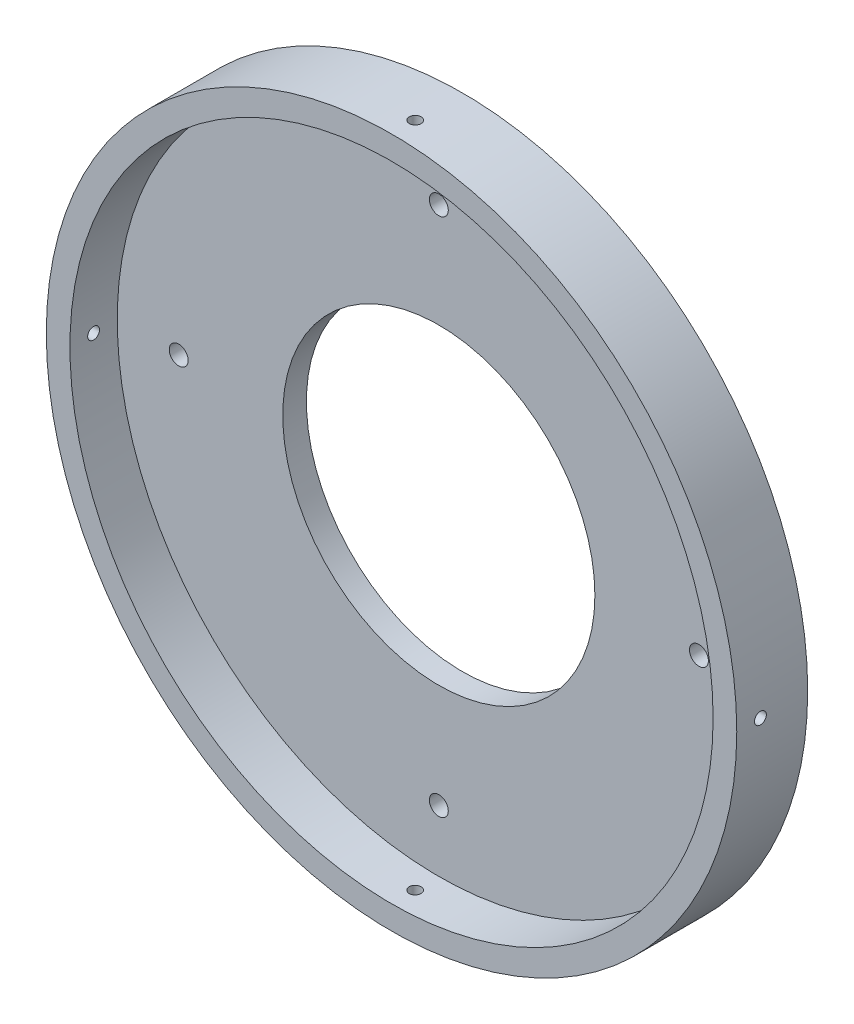
SolidWorks part; units mm, degrees
ref_plane "Front Plane" through (0, 0, 0) normal (0, 0, 1) x (1, 0, 0)
ref_plane "Top Plane" through (0, 0, 0) normal (0, 1, 0) x (1, 0, 0)
ref_plane "Right Plane" through (0, 0, 0) normal (1, 0, 0) x (0, 0, -1)
sketch "Sketch1" plane through (0, 0, 0) normal (0, 0, 1) x (1, 0, 0)
  circle A0 centre (0, 0) radius 73
  circle A1 centre (0, 0) radius 33
  dimension "D1" = 146
  dimension "D2" = 40
extrude "Boss-Extrude1" add sketch "Sketch1" along normal blind 5
sketch "Sketch2" plane through (0, 0, 5) normal (0, 0, 1) x (1, 0, 0)
  circle A0 centre (0, 0) radius 68
  circle A1 centre (0, 0) radius 73
  circle A2 centre (0, 0) radius 73
  dimension "D1" = 0
  dimension "D2" = 5
extrude "Boss-Extrude2" add sketch "Sketch2" along normal blind 10
sketch "Sketch3" plane through (0, 0, 0) normal (0, 1, 0) x (1, 0, 0)
  line L0 (-73, -15) -> (73, -15) construction
  circle A0 centre (0, -10) radius 1.25
  dimension "D2" = 2.5
  dimension "D1" = 5
extrude "Cut-Extrude1" cut sketch "Sketch3" against normal up to surface (73 mm away)
pattern_circular "CirPattern1" count 4 over 360 about axis through (0, 0, 5) along (0, 0, -1) of "Cut-Extrude1"
sketch "Sketch9" plane through (0, 0, 0) normal (0, 0, -1) x (-1, 0, 0)
  point P0 (0, 55)
  point P4 (55, 0)
  point P6 (0, -55)
  point P8 (-55, 0)
  dimension "D1" = 55
  dimension "D2" = 0
  dimension "D3" = 55
  dimension "D4" = 55
  dimension "D5" = 55
hole_wizard "Ø4.0mm Dowel Hole1" positions "Sketch9" profile "Sketch10" hole size "Ø4.0" standard "ISO" end condition through all
sketch "Sketch10" plane through (0, 55, 0) normal (1, 0, 0) x (0, 1, 0)
  line L0 (0, 0) -> (0, 15)
  line L1 (0, 15) -> (2, 15)
  line L2 (2, 15) -> (2, 0)
  line L5 (2, 0) -> (0, 0)
  line L11 (0, -6.35) -> (0, 107.95) construction
  dimension "Thru Hole Dia." = 4
  dimension "Thru Hole Depth" = 15
